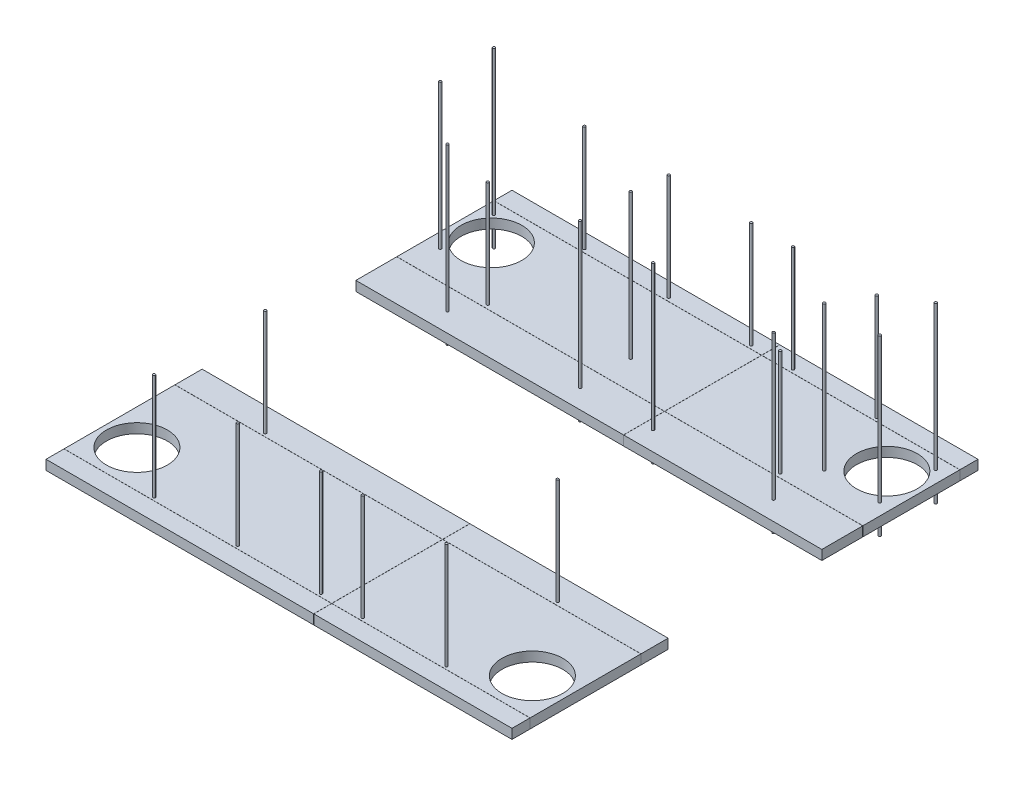
SolidWorks part; units mm, degrees
ref_plane "Front" through (0, 0, 0) normal (0, 0, 1) x (1, 0, 0)
ref_plane "Top" through (0, 0, 0) normal (0, 1, 0) x (1, 0, 0)
ref_plane "Right" through (0, 0, 0) normal (1, 0, 0) x (0, 0, -1)
sketch "Sketch1" plane through (0, 0, 0) normal (0, 1, 0) x (1, 0, 0)
  line L1 (-2454.275, 2454.275) -> (2454.275, 2454.275)
  line L2 (-2454.275, 2454.275) -> (-2454.275, -2454.275)
  line L3 (-2454.275, -2454.275) -> (2454.275, -2454.275)
  line L4 (2454.275, 2454.275) -> (2454.275, -2454.275)
  line L5 (-2454.275, 2454.275) -> (2454.275, -2454.275) construction
  line L6 (-2454.275, -2454.275) -> (2454.275, 2454.275) construction
  point P0 (0, 0)
  dimension "D1" = 4908.55
  dimension "D2" = 4908.55
extrude "Boss-Extrude1" add sketch "Sketch1" along normal blind 101.6
sketch "Sketch2" plane through (0, 101.6, 0) normal (0, 1, 0) x (1, 0, 0)
  line L0 (-2454.275, 2454.275) -> (-2454.275, -2454.275) construction
  line L1 (2454.275, -809.625) -> (-2454.275, -809.625)
  line L2 (2454.275, -809.625) -> (2454.275, 809.625)
  line L3 (2454.275, 809.625) -> (-2454.275, 809.625)
  line L4 (-2454.275, -809.625) -> (-2454.275, 809.625)
  line L5 (2454.275, -809.625) -> (-2454.275, 809.625) construction
  line L6 (2454.275, 809.625) -> (-2454.275, -809.625) construction
  point P0 (0, 0)
  dimension "D1" = 1619.25
extrude "Cut-Extrude1" cut sketch "Sketch2" against normal through all
sketch "Sketch4" plane through (0, 101.6, 0) normal (0, 1, 0) x (1, 0, 0)
  line L0 (-2454.275, -2263.775) -> (2454.275, -2263.775)
  line L3 (-2454.275, -2454.275) -> (2454.275, -2454.275) construction
  line L4 (-2454.275, -1095.375) -> (2454.275, -1095.375)
  line L5 (-2454.275, -809.625) -> (-2454.275, -2454.275) construction
  line L6 (-2454.275, -809.625) -> (2454.275, -809.625) construction
  line L7 (-2454.275, 2263.775) -> (2454.275, 2263.775)
  line L10 (-2454.275, 1241.425) -> (2454.275, 1241.425)
  line L11 (-2454.275, 2454.275) -> (-2454.275, 809.625) construction
  line L12 (2454.275, 809.625) -> (2454.275, 2454.275) construction
  line L13 (2454.275, 2454.275) -> (-2454.275, 2454.275) construction
  line L14 (2454.275, 809.625) -> (-2454.275, 809.625) construction
  line L15 (-2454.275, -1095.375) -> (-2454.275, -2263.775) construction
  line L16 (2454.275, -1095.375) -> (2454.275, -2263.775) construction
  line L17 (2454.275, 1241.425) -> (2454.275, 2263.775) construction
  line L18 (-2454.275, 1241.425) -> (-2454.275, 2263.775) construction
  line L19 (2454.275, -2454.275) -> (2454.275, -809.625) construction
  dimension "D1" = 190.5
  dimension "D2" = 1168.4
  dimension "D3" = 285.75
  dimension "D4" = 190.5
  dimension "D5" = 1022.35
  dimension "D6" = 431.8
extrude "Cut-Extrude-Thin1" cut sketch "Sketch4" against normal through all thin
sketch "Sketch5" plane through (0, 101.6, 0) normal (0, 1, 0) x (1, 0, 0)
  line L0 (365.125, -2454.275) -> (365.125, 2454.275)
  line L1 (-2454.275, -2454.275) -> (2454.275, -2454.275) construction
  line L2 (2454.275, 2454.275) -> (-2454.275, 2454.275) construction
  line L3 (2454.275, -2263.775) -> (2454.275, -1096.645) construction
  line L4 (-2454.275, -1096.645) -> (-2454.275, -2263.775) construction
  dimension "D1" = 2089.15
  dimension "D2" = 2819.4
extrude "Cut-Extrude-Thin2" cut sketch "Sketch5" against normal through all and the other way through all thin
sketch "Sketch3" plane through (0, 101.6, 0) normal (0, 1, 0) x (1, 0, 0)
  line L1 (-2276.475, -2263.775) -> (-1520.6938, -2263.775)
  line L2 (-2276.475, -2263.775) -> (-2276.475, -1507.9938)
  line L3 (-2276.475, -1507.9938) -> (-1520.6938, -1507.9938)
  line L4 (-1520.6938, -2263.775) -> (-1520.6938, -1507.9938)
  line L5 (2276.475, -2263.775) -> (1520.6938, -2263.775)
  line L6 (2276.475, -2263.775) -> (2276.475, -1507.9938)
  line L7 (2276.475, -1507.9938) -> (1520.6938, -1507.9938)
  line L8 (1520.6938, -2263.775) -> (1520.6938, -1507.9938)
  line L9 (-2276.475, 2263.775) -> (-1520.6938, 2263.775)
  line L10 (-2276.475, 2263.775) -> (-2276.475, 1507.9938)
  line L11 (-2276.475, 1507.9938) -> (-1520.6938, 1507.9938)
  line L12 (-1520.6938, 2263.775) -> (-1520.6938, 1507.9938)
  line L13 (2276.475, 2263.775) -> (1520.6938, 2263.775)
  line L14 (2276.475, 2263.775) -> (2276.475, 1507.9938)
  line L15 (2276.475, 1507.9938) -> (1520.6938, 1507.9938)
  line L16 (1520.6938, 2263.775) -> (1520.6938, 1507.9938)
  line L19 (2454.275, -2263.775) -> (2454.275, -1096.645) construction
  line L20 (366.395, -2263.775) -> (2454.275, -2263.775) construction
  line L21 (-2454.275, -2263.775) -> (365.125, -2263.775) construction
  line L22 (-2454.275, -1096.645) -> (-2454.275, -2263.775) construction
  line L23 (366.395, 2263.775) -> (2454.275, 2263.775) construction
  line L24 (2454.275, 1241.425) -> (2454.275, 2262.505) construction
  line L25 (-2454.275, 2262.505) -> (-2454.275, 1241.425) construction
  line L26 (-2454.275, 2263.775) -> (365.125, 2263.775) construction
  dimension "D1" = 177.8
  dimension "D2" = 177.8
  dimension "D3" = 177.8
  dimension "D4" = 177.8
extrude "SQUARE HOLE" [suppressed] cut sketch "Sketch3" against normal through all
sketch "Sketch6" plane through (0, 101.6, 0) normal (0, 1, 0) x (1, 0, 0)
  line L0 (2082.8, 1865.63) -> (2082.8, 2262.505) construction
  line L1 (-2082.8, 1865.63) -> (2082.8, 1865.63) construction
  line L2 (-2082.8, 1865.63) -> (-2082.8, -1868.17) construction
  line L3 (-2082.8, -1868.17) -> (2082.8, -1868.17) construction
  line L4 (2082.8, 1865.63) -> (2082.8, -1868.17) construction
  line L5 (-2082.8, -1868.17) -> (-2082.8, -2265.045) construction
  line L6 (-2454.275, -2265.045) -> (365.125, -2265.045) construction
  line L7 (366.395, 2262.505) -> (2454.275, 2262.505) construction
  line L9 (2454.275, 1241.425) -> (2454.275, 2262.505) construction
  line L11 (-2454.275, -1096.645) -> (-2454.275, -2263.775) construction
  circle A0 centre (2082.8, 1865.63) radius 320.675
  circle A1 centre (-2082.8, 1865.63) radius 320.675
  circle A2 centre (-2082.8, -1868.17) radius 320.675
  circle A3 centre (2082.8, -1868.17) radius 320.675
  dimension "D1" = 641.35
  dimension "D3" = 50.8
  dimension "D4" = 50.8
  dimension "D2" = 76.2
extrude "Cut-Extrude2" cut sketch "Sketch6" against normal through all
sketch "Sketch7" plane through (0, 101.6, 0) normal (0, 1, 0) x (1, 0, 0)
  line L0 (-1539.875, 2301.875) -> (-295.275, 2301.875) construction
  line L1 (-1539.875, 2301.875) -> (-2454.275, 2301.875) construction
  line L2 (-2454.275, 2454.275) -> (-2454.275, 2263.775) construction
  line L3 (365.125, 2454.275) -> (-2454.275, 2454.275) construction
  line L4 (-295.275, 2301.875) -> (365.125, 2301.875) construction
  line L5 (365.125, 2263.775) -> (365.125, 2454.275) construction
  line L6 (1743.075, 1546.225) -> (1743.075, 1012.825) construction
  line L7 (365.125, 2301.875) -> (974.725, 2301.875) construction
  line L8 (974.725, 2301.875) -> (1743.075, 2301.875) construction
  line L9 (1743.075, 2301.875) -> (2454.275, 2301.875) construction
  line L10 (2454.275, 2263.775) -> (2454.275, 2454.275) construction
  line L11 (366.395, 2263.775) -> (366.395, 2454.275) construction
  line L12 (2454.275, 1546.225) -> (-2454.275, 1546.225) construction
  line L13 (2454.275, 1241.425) -> (2454.275, 2262.505) construction
  line L14 (-2454.275, 2262.505) -> (-2454.275, 1241.425) construction
  line L15 (1743.075, 2301.875) -> (1743.075, 1546.225) construction
  line L16 (-2454.275, 1241.425) -> (365.125, 1241.425) construction
  line L17 (-295.275, 2301.875) -> (-295.275, 1546.225) construction
  line L18 (974.725, 2301.875) -> (974.725, 1546.225) construction
  line L19 (-2454.275, 2136.775) -> (2454.275, 2136.775) construction
  line L20 (-2454.275, 2263.775) -> (365.125, 2263.775) construction
  line L21 (-1539.875, 2301.875) -> (-1539.875, 2136.775) construction
  line L22 (-2454.275, 1012.825) -> (2454.275, 1012.825) construction
  line L23 (-2454.275, 1240.155) -> (-2454.275, 809.625) construction
  line L24 (2454.275, 809.625) -> (2454.275, 1240.155) construction
  line L25 (365.125, 809.625) -> (-2454.275, 809.625) construction
  line L26 (-1692.275, 1012.825) -> (-1692.275, 1546.225) construction
  line L27 (-295.275, 1546.225) -> (-295.275, 1012.825) construction
  line L28 (-2107.4102, -2022.1425) -> (-2107.4102, -819.4758) construction
  line L29 (-1539.875, 1285.875) -> (1539.875, 1285.875) construction
  circle A0 centre (-1539.875, 2301.875) radius 12.7
  circle A4 centre (1743.075, 1546.225) radius 12.7
  circle A5 centre (-1692.275, 1546.225) radius 12.7 construction
  circle A6 centre (473.075, 1012.825) radius 12.7
  circle A7 centre (-295.275, 1546.225) radius 12.7
  circle A8 centre (974.725, 1546.225) radius 12.7 construction
  circle A9 centre (-295.275, 2136.775) radius 12.7 construction
  circle A10 centre (-1539.875, 2136.775) radius 12.7 construction
  circle A11 centre (974.725, 2136.775) radius 12.7 construction
  circle A12 centre (1743.075, 2136.775) radius 12.7 construction
  circle A13 centre (-295.275, 1012.825) radius 12.7
  circle A14 centre (-1692.275, 1012.825) radius 12.7
  circle A15 centre (1743.075, 1012.825) radius 12.7
  circle A16 centre (-2301.875, 1546.225) radius 12.7
  circle A17 centre (2327.275, 1546.225) radius 12.7
  circle A18 centre (-2327.275, 2136.775) radius 12.7
  circle A19 centre (2327.275, 2136.775) radius 12.7
  circle A20 centre (219.075, 2301.875) radius 12.7
  circle A21 centre (658.495, 2301.875) radius 12.7
  circle A22 centre (1539.875, 2301.875) radius 12.7
  circle A23 centre (-650.875, 2301.875) radius 12.7
  circle A24 centre (-1539.875, 1285.875) radius 12.7
  circle A25 centre (1539.875, 1285.875) radius 12.7
  circle A26 centre (-1539.875, -1058.596) radius 12.7
  circle A27 centre (-1539.875, -2230.2499) radius 12.7
  circle A28 centre (-658.766, -2230.2499) radius 12.7
  circle A29 centre (219.075, -2230.2499) radius 12.7
  circle A30 centre (658.495, -2230.2499) radius 12.7
  circle A31 centre (1539.875, -2230.2499) radius 12.7
  circle A32 centre (1539.875, -1058.596) radius 12.7
  dimension "D1" = 25.4
  dimension "D5" = 609.6
  dimension "D7" = 304.8
  dimension "D11" = 127
  dimension "D14" = 152.4
  dimension "D19" = 889
  dimension "D20" = 914.4
  dimension "D21" = 1168.4
  dimension "D2" = 152.4
  dimension "D3" = 914.4
  dimension "D4" = 660.4
  dimension "D6" = 711.2
  dimension "D8" = 762
  dimension "D9" = 127
  dimension "D10" = 127
  dimension "D12" = 203.2
  dimension "D13" = 1981.2
  dimension "D15" = 127
  dimension "D16" = 146.05
  dimension "D17" = 292.1
  dimension "D18" = 914.4
  dimension "D22" = 3079.75
extrude "STUD LAYOUT SKETCH" add sketch "Sketch7" along normal blind 1524 and the other way blind 304.8 separate body
sketch "Sketch8" plane through (0, 1625.6, 0) normal (0, 1, 0) x (1, 0, 0)
  line L1 (-2748.8936, 3759.21) -> (2748.8936, 3759.21)
  line L2 (-2748.8936, 3759.21) -> (-2748.8936, -3759.21)
  line L3 (-2748.8936, -3759.21) -> (2748.8936, -3759.21)
  line L4 (2748.8936, 3759.21) -> (2748.8936, -3759.21)
  line L5 (-2748.8936, 3759.21) -> (2748.8936, -3759.21) construction
  line L6 (-2748.8936, -3759.21) -> (2748.8936, 3759.21) construction
  point P0 (0, 0)
  dimension "D1" = 7518.42
  dimension "D2" = 5497.7872
sketch "Sketch9" plane through (0, -203.2, 0) normal (0, -1, 0) x (1, 0, 0)
  line L1 (2592.4344, 3685.246) -> (-2592.4344, 3685.246)
  line L2 (2592.4344, 3685.246) -> (2592.4344, -3685.246)
  line L3 (2592.4344, -3685.246) -> (-2592.4344, -3685.246)
  line L4 (-2592.4344, 3685.246) -> (-2592.4344, -3685.246)
  line L5 (2592.4344, 3685.246) -> (-2592.4344, -3685.246) construction
  line L6 (2592.4344, -3685.246) -> (-2592.4344, 3685.246) construction
  point P0 (0, 0)
  dimension "D1" = 7370.492
  dimension "D2" = 5184.8688
extrude "Cut-Extrude5" cut sketch "Sketch8" against normal blind 406.4
extrude "Cut-Extrude6" cut sketch "Sketch9" against normal blind 254
